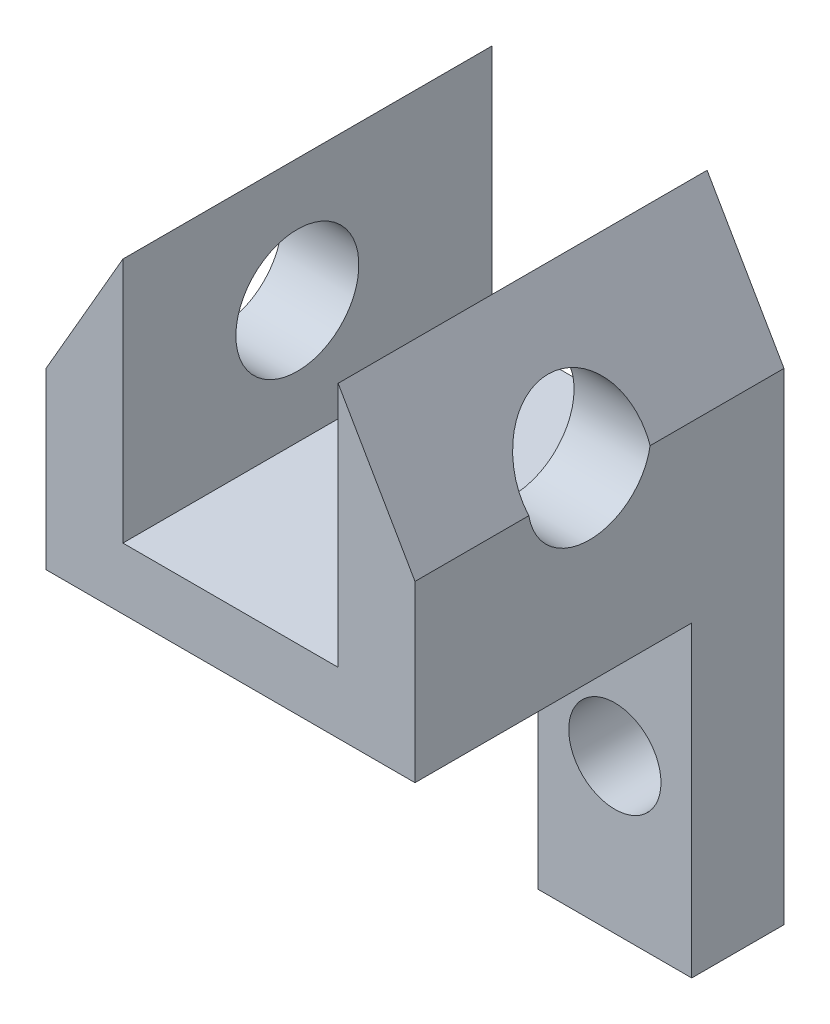
SolidWorks part; units mm, degrees
ref_plane "Front Plane" through (0, 0, 0) normal (0, 0, 1) x (1, 0, 0)
ref_plane "Top Plane" through (0, 0, 0) normal (0, 1, 0) x (1, 0, 0)
ref_plane "Right Plane" through (0, 0, 0) normal (1, 0, 0) x (0, 0, -1)
sketch "Sketch1" plane through (0, 0, 0) normal (0, 1, 0) x (1, 0, 0)
  line L1 (-6, -6) -> (6, -6)
  line L2 (-6, -6) -> (-6, 6)
  line L3 (-6, 6) -> (6, 6)
  line L4 (6, -6) -> (6, 6)
  line L5 (-6, -6) -> (6, 6) construction
  line L6 (-6, 6) -> (6, -6) construction
  point P0 (0, 0)
  dimension "D1" = 12
  dimension "D2" = 12
extrude "Boss-Extrude1" add sketch "Sketch1" along normal blind 2
sketch "Sketch2" plane through (0, 2, 0) normal (0, 1, 0) x (1, 0, 0)
  line L0 (-6, -6) -> (6, -6) construction
  line L1 (-6, 6) -> (-3.5, 6)
  line L2 (-6, 6) -> (-6, -6)
  line L3 (-6, -6) -> (-3.5, -6)
  line L4 (-3.5, 6) -> (-3.5, -6)
  line L5 (6, 6) -> (-6, 6) construction
  line L6 (6, -6) -> (3.5, -6)
  line L7 (6, -6) -> (6, 6)
  line L8 (6, 6) -> (3.5, 6)
  line L9 (3.5, -6) -> (3.5, 6)
  line L10 (-3.5, 6) -> (3.5, 6) construction
  line L11 (-6, 6) -> (6, 6) construction
  point P16 (0, 6)
  point P17 (0, 6)
  dimension "D1" = 7
extrude "Boss-Extrude2" add sketch "Sketch2" along normal blind 8
sketch "Sketch4" plane through (3.5, 0, 0) normal (-1, 0, 0) x (0, 0, 1)
  line L0 (-6, 2) -> (6, 2) construction
  circle A0 centre (0.3261, 6) radius 2
  dimension "D1" = 4
  dimension "D2" = 4
sketch "Sketch5" plane through (0, 0, 6) normal (0, 0, 1) x (1, 0, 0)
  line L0 (-3.5, 10) -> (-6, 5.6699)
  line L1 (-3.5, 10) -> (-3.5, 2) construction
  line L2 (-6, 10) -> (-6, 0) construction
  line L3 (0, 0) -> (0, 10.4395) construction
  line L4 (3.5, 10) -> (6, 5.6699)
  line L5 (3.5, 10) -> (3.5, 2) construction
  line L6 (6, 10) -> (6, 0) construction
  line L7 (3.5, 10) -> (6, 10)
  line L8 (6, 10) -> (6, 5.6699)
  line L9 (-6, 10) -> (-6, 5.6699)
  line L10 (-3.5, 10) -> (-6, 10)
  dimension "D1" = 30
  dimension "D2" = 30
extrude "Cut-Extrude1" cut sketch "Sketch5" against normal through all
extrude "Cut-Extrude2" cut sketch "Sketch4" against normal through all and the other way through all
sketch "Sketch6" plane through (0, 0, 0) normal (0, -1, 0) x (1, 0, 0)
  line L1 (6, -6) -> (1, -6)
  line L2 (6, -6) -> (6, -3)
  line L3 (6, -3) -> (1, -3)
  line L4 (1, -6) -> (1, -3)
  dimension "D1" = 5
  dimension "D2" = 3
extrude "Boss-Extrude3" add sketch "Sketch6" along normal blind 10
ref_point "Point1"
hole_wizard "Ø3.0mm Dowel Hole1" positions "Sketch7" profile "Sketch8" hole size "Ø3.0" standard "ANSI Metric"
sketch "Sketch7" plane through (0, 0, -3) normal (0, 0, 1) x (1, 0, 0)
  point P0 (3.5, -5)
sketch "Sketch8" plane through (3.5, -5, -3) normal (1, 0, 0) x (0, -1, 0)
  line L0 (0, 0) -> (0, 3.9013)
  line L1 (0, 3.9013) -> (1.5, 3)
  line L2 (1.5, 3) -> (1.5, 0)
  line L5 (1.5, 0) -> (0, 0)
  line L10 (0, 3.9013) -> (-1.5, 3) construction
  line L11 (0, -6.35) -> (0, 107.95) construction
  dimension "Hole Dia." = 3
  dimension "Hole Depth" = 3
  dimension "Drill Angle" = 118
